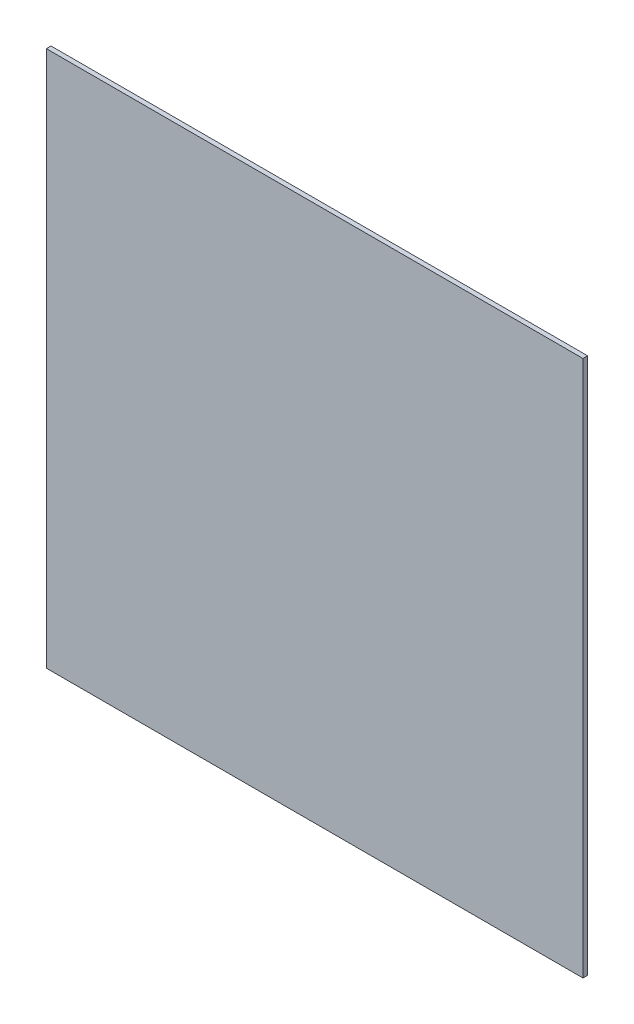
SolidWorks part; units mm, degrees
material "PMMA"
ref_plane "Front Plane" through (0, 0, 0) normal (0, 0, 1) x (1, 0, 0)
ref_plane "Top Plane" through (0, 0, 0) normal (0, 1, 0) x (1, 0, 0)
ref_plane "Right Plane" through (0, 0, 0) normal (1, 0, 0) x (0, 0, -1)
sketch "Sketch1" plane through (0, 0, 0) normal (0, 0, 1) x (1, 0, 0)
  line L1 (-63.65, 127.3) -> (63.65, 127.3)
  line L2 (-63.65, 127.3) -> (-63.65, 0)
  line L3 (-63.65, 0) -> (63.65, 0)
  line L4 (63.65, 127.3) -> (63.65, 0)
  point P4 (0, 0)
  dimension "D1" = 127.3
  dimension "D2" = 127.3
extrude "Boss-Extrude1" add sketch "Sketch1" along normal blind 1.1
